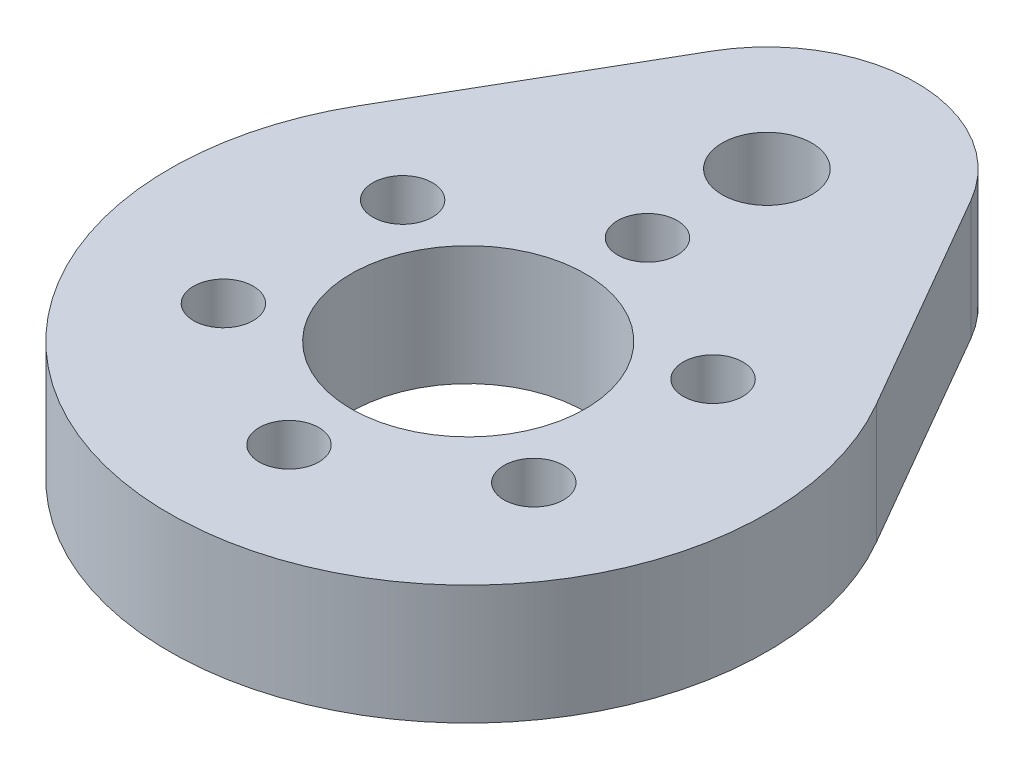
SolidWorks part; units mm, degrees
ref_plane "Front Plane" through (0, 0, 0) normal (0, 0, 1) x (1, 0, 0)
ref_plane "Top Plane" through (0, 0, 0) normal (0, 1, 0) x (1, 0, 0)
ref_plane "Right Plane" through (0, 0, 0) normal (1, 0, 0) x (0, 0, -1)
sketch "Sketch1" plane through (0, 0, 0) normal (0, 1, 0) x (1, 0, 0)
  line L0 (-5.4993, 15.875) -> (-10.9985, 6.35)
  line L1 (5.4993, 15.875) -> (10.9985, 6.35)
  line L2 (0, 0) -> (0, 12.7) construction
  arc A0 (-10.9985, 6.35) -> (10.9985, 6.35) centre (0, 0) ccw
  circle A1 centre (0, 0) radius 4.9792
  circle A2 centre (0, 7.62) radius 1.27
  circle A3 centre (6.5991, 3.81) radius 1.27
  circle A4 centre (6.5991, -3.81) radius 1.27
  circle A5 centre (0, -7.62) radius 1.27
  circle A6 centre (-6.5991, -3.81) radius 1.27
  circle A7 centre (-6.5991, 3.81) radius 1.27
  circle A8 centre (0, 12.7) radius 1.905
  arc A9 (5.4993, 15.875) -> (-5.4993, 15.875) centre (0, 12.7) ccw
  circle A10 centre (0, 0) radius 7.62 construction
  point P6 (-11.0644, 6.2345)
  point P18 (0, 0)
  point P24 (-11.7035, 4.9314)
  point P25 (0, 0)
  dimension "D3" = 3.81
  dimension "D4" = 6.35
  dimension "D5" = 12.7
  dimension "D6" = 15.24
  dimension "D7" = 2.54
  dimension "D2" = 12.7
  dimension "D1" = 6
extrude "Boss-Extrude1" add sketch "Sketch1" along normal blind 5.08
